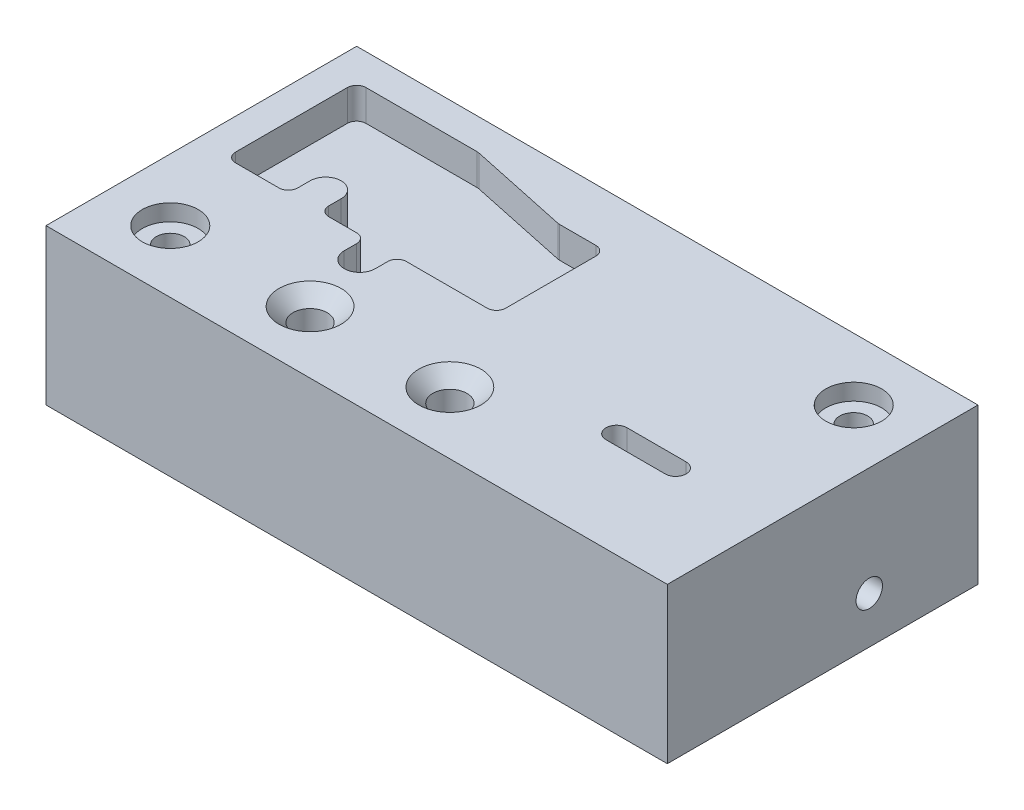
SolidWorks part; units mm, degrees
material "Plain Carbon Steel"
ref_plane "Front Plane" through (0, 0, 0) normal (0, 0, 1) x (1, 0, 0)
ref_plane "Top Plane" through (0, 0, 0) normal (0, 1, 0) x (1, 0, 0)
ref_plane "Right Plane" through (0, 0, 0) normal (1, 0, 0) x (0, 0, -1)
other "Configuration Table"
sketch "Sketch1" plane through (0, 0, 0) normal (0, 1, 0) x (1, 0, 0)
  line L0 (-100, 50) -> (100, -50) construction
  line L1 (-100, 50) -> (100, 50)
  line L2 (-100, 50) -> (-100, -50)
  line L3 (-100, -50) -> (100, -50)
  line L4 (100, 50) -> (100, -50)
  dimension "D1" = 200
  dimension "D2" = 100
extrude "Block Stock" add sketch "Sketch1" along normal blind 50
hole_wizard "M10 Tapped Hole1" positions "Sketch5" profile "Sketch4" tap size "M10" standard "ISO"
sketch "Sketch5" plane through (100, 0, 0) normal (1, 0, 0) x (0, 0, -1)
  line L0 (50, 50) -> (50, 0) construction
  line L1 (-50, 0) -> (50, 0) construction
  point P1 (15, 15)
  dimension "D1" = 35
  dimension "D2" = 15
sketch "Sketch4" plane through (100, 15, -15) normal (0, 1, 0) x (0, 0, -1)
  line L0 (0, 0) -> (0, 27.5537)
  line L1 (0, 27.5537) -> (4.25, 25)
  line L2 (4.25, 25) -> (4.25, 0)
  line L5 (4.25, 0) -> (0, 0)
  line L10 (0, 27.5537) -> (-4.25, 25) construction
  line L11 (0, -6.35) -> (0, 107.95) construction
  dimension "Tap Drill Dia." = 8.5
  dimension "Tap Drill Depth" = 25
  dimension "Drill Angle" = 118
cosmetic thread "Hole Thread1" parameters "D1"=20, "D2"=10
hole_wizard "CBORE for M8 Hex Head Bolt1" positions "Sketch7" profile "Sketch6" counterbore size "M8" standard "ISO" end condition through all
sketch "Sketch7" plane through (0, 50, 0) normal (0, 1, 0) x (-1, 0, 0)
  line L0 (100, 50) -> (-100, 50) construction
  line L1 (100, -50) -> (100, 50) construction
  line L2 (-100, 50) -> (-100, -50) construction
  line L3 (-100, -50) -> (100, -50) construction
  point P0 (80, 30)
  point P5 (-80, -30)
  dimension "D1" = 20
  dimension "D2" = 20
  dimension "D3" = 20
  dimension "D4" = 20
sketch "Sketch6" plane through (-80, 50, 30) normal (1, 0, 0) x (0, 0, 1)
  line L0 (0, 0) -> (0, 50)
  line L1 (0, 50) -> (4.5, 50)
  line L3 (4.5, 50) -> (4.5, 5.3)
  line L4 (4.5, 5.3) -> (9.0055, 5.3)
  line L5 (9.0055, 5.3) -> (9.0055, 0)
  line L7 (9.0055, 0) -> (0, 0)
  line L11 (0, -6.35) -> (0, 107.95) construction
  dimension "Thru Hole Dia." = 9
  dimension "Thru Hole Depth" = 50
  dimension "C'Bore Dia." = 18.011
  dimension "C'Bore Depth" = 5.3
sketch "Sketch10" plane through (0, 50, 0) normal (0, 1, 0) x (1, 0, 0)
  line L0 (100, 50) -> (-100, 50) construction
  line L1 (-100, 50) -> (-100, -50) construction
  circle A0 centre (30, 25) radius 3
  dimension "D1" = 6
  dimension "D3" = 130
  dimension "D2" = 25
extrude "PreCut for ISO11926" [suppressed] cut sketch "Sketch10" against normal blind 6
sketch "Drop location" [suppressed] plane through (-13.369, 50, 9.7542) normal (0, 1, 0) x (1, 0, 0)
  line L0 (0, 0) -> (-31.7732, 0) construction
  circle A1 centre (18.369, 34.7542) radius 3 construction
  point P0 (18.369, 34.7542)
ref_plane "Plane1" [suppressed] through (5, 50, -25) normal (-1, 0, 0) x (0, 0, 1)
sketch "Port Sketch" [suppressed] plane through (5, 50, 0) normal (1, 0, 0) x (0, 0, 1)
  line L0 (-25, 0) -> (-25, 53.9676) construction
  line L1 (-25, 19.0576) -> (-19.2456, 15.6)
  line L2 (-19.2456, 15.6) -> (-19.2456, 13.1)
  line L3 (-19.2456, 13.1) -> (-18.65, 13.1)
  line L4 (-18.65, 13.1) -> (-18.65, 3.9592)
  line L5 (-18.65, 3.9592) -> (-18.6908, 4)
  line L6 (-18.6908, 4) -> (-18.2234, 1.8012)
  line L7 (-17.975, 1.6) -> (-13.5, 1.6)
  line L8 (-13.5, 1.6) -> (-13.5, 0)
  line L10 (-13.5, 0) -> (-25, 0)
  line L11 (-25, 0) -> (-25, 19.0576)
  line L12 (-31.3092, 4) -> (-31.7766, 1.8012) construction
  line L13 (-31.35, 3.9592) -> (-31.3092, 4) construction
  line L14 (-25, 19.0576) -> (-30.7544, 15.6) construction
  arc A0 (-18.2234, 1.8012) -> (-17.975, 1.6) centre (-17.975, 1.854) ccw
  dimension "D1" = 0.254
  dimension "D2" = 118
  dimension "D3" = 45
  dimension "TapDrillDia" = 11.5087
  dimension "D5" = 14.05
  dimension "ThdMjr" = 12.7
  dimension "SpotDia" = 23
  dimension "L3" = 1.6
  dimension "L1" = 2.4
  dimension "ThdDp" = 11.5
  dimension "TapDrillDp" = 14
  dimension "K" = 12
revolve "SAE Port" [suppressed] cut sketch "Port Sketch" angle 360 about L0
other "iso 11926-1 fluid power port<1>" [suppressed]
sketch "Sketch2" plane through (0, 50, 0) normal (0, 1, 0) x (1, 0, 0)
  line L0 (-100, 50) -> (-100, -50) construction
  line L1 (-87, 40) -> (-51.2477, 40)
  line L2 (-90, 37) -> (-90, 1)
  line L3 (-87, -2) -> (-73, -2)
  line L4 (-70, 1) -> (-70, 5)
  line L5 (100, 50) -> (-100, 50) construction
  line L6 (-50.624, 39.9344) -> (-18.3084, 33.0656)
  line L7 (-60, 5) -> (-60, 1)
  line L8 (-17.6847, 33) -> (-6, 33)
  line L9 (-3, 30) -> (-3, 1)
  line L10 (-45, -5) -> (-45, -9)
  line L11 (-35, -9) -> (-35, -5)
  line L12 (-57, -2) -> (-48, -2)
  line L13 (-32, -2) -> (-6, -2)
  arc A0 (-87, 40) -> (-90, 37) centre (-87, 37) ccw
  arc A1 (-3, 30) -> (-6, 33) centre (-6, 30) ccw
  arc A2 (-6, -2) -> (-3, 1) centre (-6, 1) ccw
  arc A3 (-90, 1) -> (-87, -2) centre (-87, 1) ccw
  arc A4 (-18.3084, 33.0656) -> (-17.6847, 33) centre (-17.6847, 36) ccw
  arc A5 (-50.624, 39.9344) -> (-51.2477, 40) centre (-51.2477, 37) ccw
  arc A6 (-70, 5) -> (-60, 5) centre (-65, 5) cw
  arc A7 (-45, -9) -> (-35, -9) centre (-40, -9) ccw
  arc A8 (-35, -5) -> (-32, -2) centre (-32, -5) cw
  arc A9 (-45, -5) -> (-48, -2) centre (-48, -5) ccw
  arc A10 (-60, 1) -> (-57, -2) centre (-57, 1) ccw
  arc A11 (-70, 1) -> (-73, -2) centre (-73, 1) cw
  point P10 (-90, 40)
  point P17 (-90, -2)
  point P24 (-18, 33)
  point P37 (-35, -2)
  point P40 (-45, -2)
  point P43 (-60, -2)
  dimension "D5" = 3
  dimension "D4" = 12
  dimension "D6" = 12
  dimension "D7" = 10
  dimension "D8" = 10
  dimension "D1" = 10
  dimension "D2" = 10
  dimension "D3" = 42
  dimension "D9" = 87
  dimension "D10" = 35
  dimension "D11" = 12
  dimension "D12" = 15
  dimension "D13" = 15
  dimension "D14" = 20
extrude "Pocket 1" cut sketch "Sketch2" against normal blind 10
hole_wizard "CSK for M10 Cross Recess Flat Head Screw1" positions "Sketch13" profile "Sketch12" countersink size "M10" standard "IS" end condition through all
sketch "Sketch13" plane through (0, 50, 0) normal (0, 1, 0) x (-1, 0, 0)
  line L0 (100, 50) -> (-100, 50) construction
  line L1 (100, -50) -> (100, 50) construction
  point P0 (-10, 30)
  point P1 (35, 30)
  dimension "D1" = 20
  dimension "D2" = 45
  dimension "D3" = 65
sketch "Sketch12" plane through (10, 50, 30) normal (1, 0, 0) x (0, 0, 1)
  line L0 (0, 0) -> (0, 50)
  line L1 (0, 50) -> (5.5, 50)
  line L2 (5.5, 50) -> (5.5, 4.5)
  line L3 (5.5, 4.5) -> (10, 0)
  line L5 (10, 0) -> (0, 0)
  line L6 (-5.5, 4.5) -> (-10, 0) construction
  line L11 (0, -6.35) -> (0, 107.95) construction
  dimension "Thru Hole Dia." = 11
  dimension "Thru Hole Depth" = 50
  dimension "Near C'Sink Dia." = 20
  dimension "Near C'Sink Angle" = 90
sketch "SlotSke" plane through (218.7037, 50, 182.3756) normal (0, 1, 0) x (1, 0, 0)
  line L0 (-149.8268, 166.1878) -> (-168.8768, 166.1878) construction
  line L1 (-159.3518, 162.8223) -> (-159.3518, 169.5533) construction
  line L2 (-149.8268, 162.8223) -> (-168.8768, 162.8223)
  line L3 (-168.8768, 169.5533) -> (-149.8268, 169.5533)
  line L4 (-118.7037, 132.3756) -> (-118.7037, 232.3756) construction
  line L5 (-118.7037, 132.3756) -> (-318.7037, 132.3756) construction
  arc A0 (-168.8768, 162.8223) -> (-168.8768, 169.5533) centre (-168.8768, 166.1878) cw
  arc A1 (-149.8268, 162.8223) -> (-149.8268, 169.5533) centre (-149.8268, 166.1878) ccw
  point P12 (-159.3518, 166.1878)
  dimension "Length" = 19.05
  dimension "Width" = 6.731
  dimension "Locating dim1" = 40.6482
  dimension "Locating dim2" = 33.8122
extrude "Slot" cut sketch "SlotSke" against normal through all
other "straight slot<1>"
